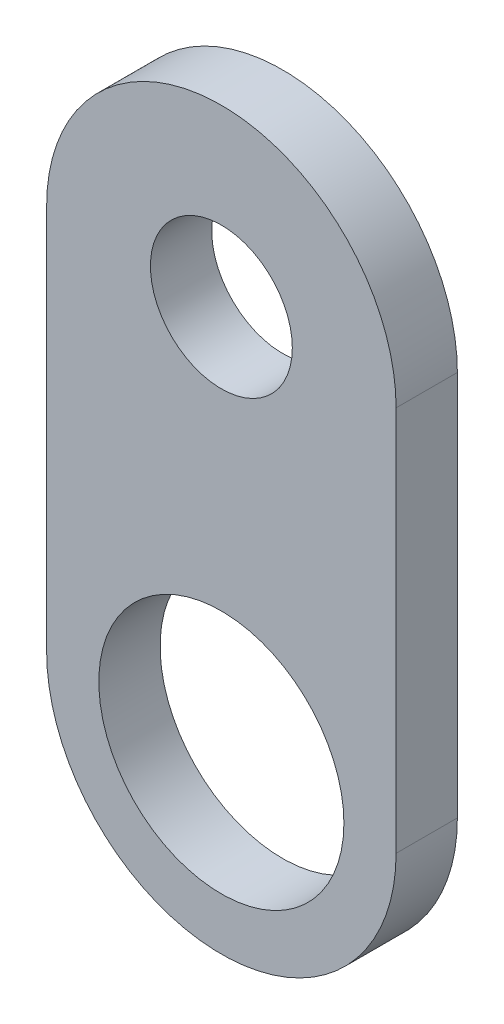
SolidWorks part; units mm, degrees
ref_plane "Front Plane" through (0, 0, 0) normal (0, 0, 1) x (1, 0, 0)
ref_plane "Top Plane" through (0, 0, 0) normal (0, 1, 0) x (1, 0, 0)
ref_plane "Right Plane" through (0, 0, 0) normal (1, 0, 0) x (0, 0, -1)
sketch "Sketch2" plane through (0, 0, 0) normal (0, 0, 1) x (1, 0, 0)
  line L2 (0, 0) -> (0, 39.9813)
  line L4 (36.2187, 0) -> (36.2187, 39.9813)
  arc A0 (0, 39.9813) -> (36.2187, 39.9813) centre (18.1093, 39.9813) cw
  arc A1 (36.2187, 0) -> (0, 0) centre (18.1093, 0) cw
  circle A2 centre (18.1093, 39.9813) radius 7.3533
  circle A3 centre (18.1093, 0) radius 12.7
  point P9 (0, 0)
  point P10 (0, 0)
  point P11 (18.1093, 58.0907)
  point P12 (18.1093, -18.1093)
  point P13 (0, 0)
  point P14 (18.1093, 39.9813)
  dimension "D1" = 25.4
  dimension "D2" = 14.7066
  dimension "D3" = 76.2
  dimension "D5" = 18.1093
extrude "Boss-Extrude1" add sketch "Sketch2" along normal blind 6.35
equation "\"L\"= 3"
equation "\"D1\"= .5790"
equation "\"Da\"= 1"
equation "\"F\"= 1200"
equation "\"AllowS\"= 9000"
equation "\"A\\\"= ( \"F\" / 2 ) / 9000"
equation "\"W\"= sqr ( \"A\\\" )"
equation "\"B\"= \"W\""
equation "\"D1@Sketch2\"=\"Da\""
equation "\"D2@Sketch2\"=\"D1\""
equation "\"D3@Sketch2\"=\"L\""
